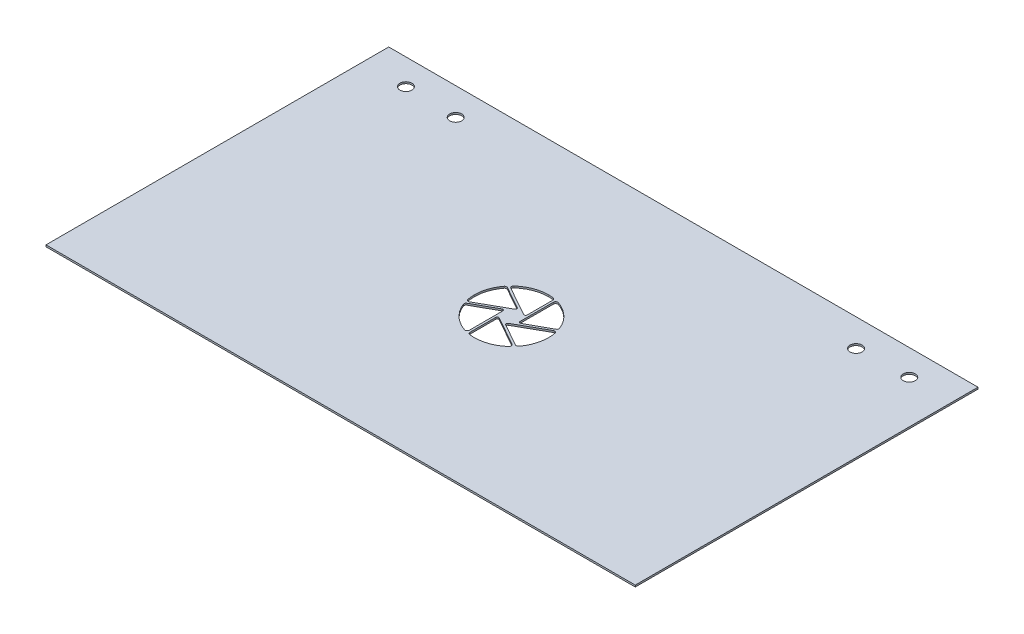
SolidWorks part; units mm, degrees
ref_plane "Front Plane" through (0, 0, 0) normal (0, 0, 1) x (1, 0, 0)
ref_plane "Top Plane" through (0, 0, 0) normal (0, 1, 0) x (1, 0, 0)
ref_plane "Right Plane" through (0, 0, 0) normal (1, 0, 0) x (0, 0, -1)
sketch "Sketch1" plane through (0, 0, 0) normal (0, 1, 0) x (1, 0, 0)
  line L0 (-7.9858, -4.6482) -> (8.711, 4.7591)
  line L1 (-160.0889, 100.2849) -> (182.9111, 100.2849)
  line L2 (-160.0889, 100.2849) -> (-160.0889, -99.2151)
  line L3 (-160.0889, -99.2151) -> (182.9111, -99.2151)
  line L4 (182.9111, 100.2849) -> (182.9111, -99.2151)
  line L5 (8.7083, 6.3003) -> (-4.2906, 13.5697)
  line L6 (17.7899, -0.5914) -> (30.8612, 6.6772)
  line L7 (16.503, 19.5582) -> (16.4766, 0.1821)
  line L8 (14.0084, -5.7683) -> (27.0112, -13.0398)
  line L9 (30.7046, 5.2041) -> (14.005, -4.2274)
  line L10 (15.3066, 5.4989) -> (15.3066, 20.4179)
  line L11 (-2.938, 14.1886) -> (13.9919, 4.7274)
  line L12 (7.3574, -4.9301) -> (7.3574, -19.8769)
  line L13 (25.658, -13.6574) -> (8.6725, -4.1587)
  line L14 (4.8479, 1.149) -> (-8.1495, -6.1197)
  line L15 (6.1589, -19.0006) -> (6.1629, 0.3775)
  line L16 (11.4111, 100.2849) -> (11.4111, -99.2151) construction
  line L17 (-160.0889, 0.5349) -> (182.9111, 0.5349) construction
  spline S0 degree 3 poles (-4.2906, 13.5697) (-4.8413, 13.8775) (-5.5352, 13.7295) (-5.9145, 13.2249) knots 0 0 0 0 1 1 1 1
  spline S1 degree 3 poles (-5.9145, 13.2249) (-8.6268, 9.6148) (-10.2375, 5.1303) (-10.2375, 0.2671) knots 1 1 1 1 2 2 2 2
  spline S2 degree 3 poles (-10.2375, 0.2671) (-10.2375, -1.1231) (-10.0953, -2.478) (-9.8379, -3.7924) knots 2 2 2 2 3 3 3 3
  spline S3 degree 3 poles (-9.8379, -3.7924) (-9.6733, -4.6343) (-8.7328, -5.0691) (-7.9858, -4.6482) knots 3 3 3 3 4 4 4 4
  spline S4 degree 3 poles (8.711, 4.7591) (9.3118, 5.0977) (9.3105, 5.9637) (8.7083, 6.3003) knots 5 5 5 5 6 6 6 6
  spline S5 degree 3 poles (30.8612, 6.6772) (31.4138, 6.9847) (31.6533, 7.6563) (31.4193, 8.2442) knots 1 1 1 1 2 2 2 2
  spline S6 degree 3 poles (31.4193, 8.2442) (29.0751, 14.1335) (24.219, 18.7372) (18.1689, 20.7458) knots 2 2 2 2 3 3 3 3
  spline S7 degree 3 poles (18.1689, 20.7458) (17.351, 21.0174) (16.5043, 20.4197) (16.503, 19.5582) knots 3 3 3 3 4 4 4 4
  spline S8 degree 3 poles (16.4766, 0.1821) (16.4759, -0.4925) (17.2003, -0.9193) (17.7899, -0.5914) knots 5 5 5 5 6 6 6 6
  spline S9 degree 3 poles (27.0112, -13.0398) (27.5615, -13.3477) (28.2554, -13.1997) (28.6344, -12.6954) knots 1 1 1 1 2 2 2 2
  spline S10 degree 3 poles (28.6344, -12.6954) (31.3494, -9.085) (32.9618, -4.5984) (32.9618, 0.2671) knots 2 2 2 2 3 3 3 3
  spline S11 degree 3 poles (32.9618, 0.2671) (32.9618, 1.6655) (32.8182, 3.0282) (32.5581, 4.35) knots 3 3 3 3 4 4 4 4
  spline S12 degree 3 poles (32.5581, 4.35) (32.3925, 5.1916) (31.4517, 5.6261) (30.7046, 5.2041) knots 4 4 4 4 5 5 5 5
  spline S13 degree 3 poles (14.005, -4.2274) (13.4049, -4.5664) (13.4066, -5.4317) (14.0084, -5.7683) knots 6 6 6 6 7 7 7 7
  spline S14 degree 3 poles (15.3066, 20.4179) (15.3066, 21.0471) (14.842, 21.5802) (14.2188, 21.6658) knots 1 1 1 1 2 2 2 2
  spline S15 degree 3 poles (14.2188, 21.6658) (13.2841, 21.7945) (12.3318, 21.867) (11.3622, 21.867) knots 2 2 2 2 3 3 3 3
  spline S16 degree 3 poles (11.3622, 21.867) (5.7581, 21.867) (0.6653, 19.7199) (-3.1707, 16.2171) knots 3 3 3 3 4 4 4 4
  spline S17 degree 3 poles (-3.1707, 16.2171) (-3.805, 15.638) (-3.6875, 14.6075) (-2.938, 14.1886) knots 4 4 4 4 5 5 5 5
  spline S18 degree 3 poles (13.9919, 4.7274) (14.5809, 4.3983) (15.3066, 4.824) (15.3066, 5.4989) knots 6 6 6 6 7 7 7 7
  spline S19 degree 3 poles (7.3574, -19.8769) (7.3578, -20.5054) (7.8214, -21.0378) (8.4439, -21.1249) knots 1 1 1 1 2 2 2 2
  spline S20 degree 3 poles (8.4439, -21.1249) (9.3979, -21.2579) (10.3708, -21.3321) (11.3618, -21.3321) knots 2 2 2 2 3 3 3 3
  spline S21 degree 3 poles (11.3618, -21.3321) (16.9642, -21.3321) (22.0546, -19.1867) (25.8903, -15.6863) knots 3 3 3 3 4 4 4 4
  spline S22 degree 3 poles (25.8903, -15.6863) (26.5246, -15.1075) (26.4074, -14.0767) (25.658, -13.6574) knots 4 4 4 4 5 5 5 5
  spline S23 degree 3 poles (8.6725, -4.1587) (8.0835, -3.8295) (7.3574, -4.2552) (7.3574, -4.9301) knots 6 6 6 6 7 7 7 7
  spline S24 degree 3 poles (-8.1495, -6.1197) (-8.7002, -6.4279) (-8.9383, -7.0974) (-8.7056, -7.684) knots 1 1 1 1 2 2 2 2
  spline S25 degree 3 poles (-8.7056, -7.684) (-6.3739, -13.5638) (-1.5385, -18.1652) (4.4899, -20.1887) knots 2 2 2 2 3 3 3 3
  spline S26 degree 3 poles (4.4899, -20.1887) (5.3088, -20.4637) (6.1589, -19.8642) (6.1589, -19.0006) knots 3 3 3 3 4 4 4 4
  spline S27 degree 3 poles (6.1629, 0.3775) (6.1633, 1.0524) (5.4372, 1.4785) (4.8479, 1.149) knots 5 5 5 5 6 6 6 6
  dimension "D1" = 343
  dimension "D2" = 199.5
extrude "Boss-Extrude1" add sketch "Sketch1" along normal blind 1
sketch "Sketch7" plane through (0, 1, 0) normal (0, 1, 0) x (1, 0, 0)
  line L0 (-160.0889, 100.2849) -> (-160.0889, -99.2151) construction
  line L1 (182.9111, 100.2849) -> (-160.0889, 100.2849) construction
  line L2 (182.9111, -99.2151) -> (182.9111, 100.2849) construction
  circle A0 centre (-135.0889, 85.2849) radius 2
  circle A1 centre (-105.1056, 84.2855) radius 2
  circle A2 centre (127.9277, 84.2855) radius 2
  circle A3 centre (157.9111, 85.2849) radius 2
  dimension "D1" = 25
  dimension "D2" = 30
  dimension "D3" = 15
  dimension "D4" = 30
  dimension "D5" = 25
  dimension "D6" = 15
hole_wizard "M6 Clearance Hole1" positions "3DSketch4" profile "Sketch9" hole size "M6" standard "ISO" end condition up to next
sketch3d "3DSketch4"
  point P0 (-135.0889, 1, -85.2849)
  point P3 (-105.1056, 1, -84.2855)
  point P6 (127.9277, 1, -84.2855)
  point P9 (157.9111, 1, -85.2849)
sketch "Sketch9" plane through (-135.0889, 1, -85.2849) normal (1, 0, 0) x (0, 0, 1)
  line L0 (0, 0) -> (0, 1)
  line L1 (0, 1) -> (3.5, 1)
  line L2 (3.5, 1) -> (3.5, 0)
  line L5 (3.5, 0) -> (0, 0)
  line L11 (0, -6.35) -> (0, 107.95) construction
  dimension "Thru Hole Dia." = 7
  dimension "Thru Hole Depth" = 1
